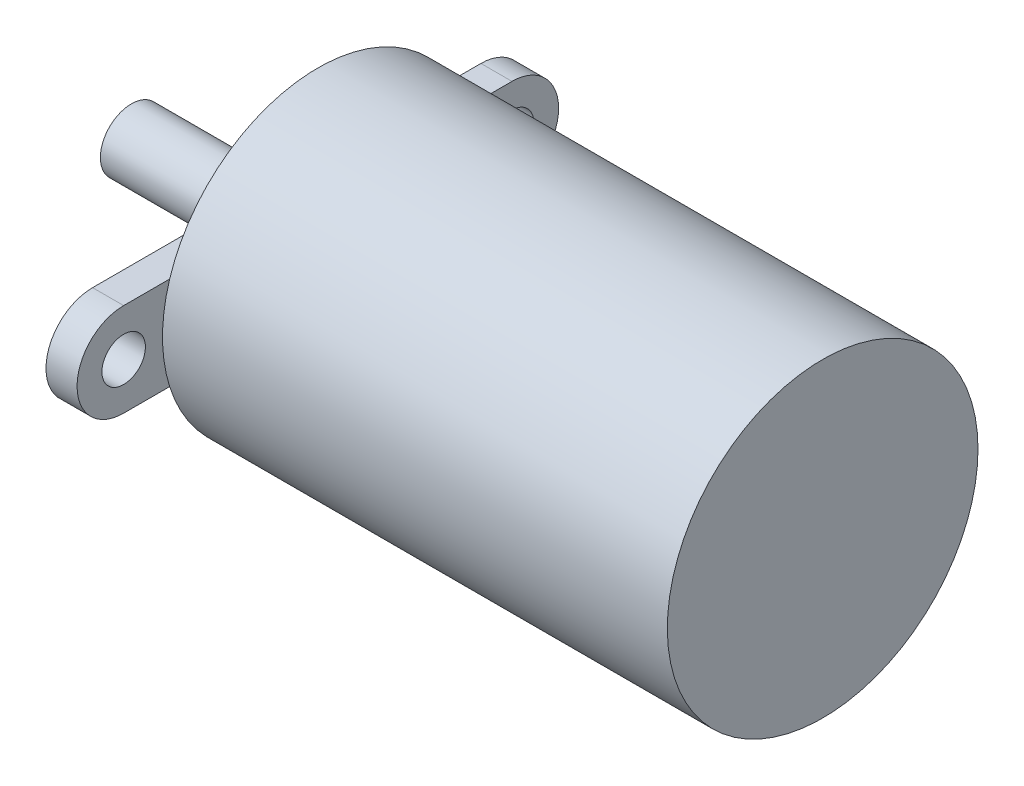
SolidWorks part; units mm, degrees
material "ABS"
ref_plane "Front" through (0, 0, 0) normal (0, 0, 1) x (1, 0, 0)
ref_plane "Top" through (0, 0, 0) normal (0, 1, 0) x (1, 0, 0)
ref_plane "Right" through (0, 0, 0) normal (1, 0, 0) x (0, 0, -1)
sketch "Sketch1" plane through (0, 0, 0) normal (1, 0, 0) x (0, 0, -1)
  circle A0 centre (0, 0) radius 10
  dimension "D1" = 20
extrude "Boss-Extrude1" add sketch "Sketch1" along normal blind 32.5
sketch "Sketch2" plane through (0, 0, 0) normal (-1, 0, 0) x (0, 0, 1)
  line L0 (-12.5, 0) -> (12.5, 0) construction
  line L1 (-12.5, 3) -> (12.5, 3)
  line L2 (-12.5, -3) -> (12.5, -3)
  arc A0 (-12.5, 3) -> (-12.5, -3) centre (-12.5, 0) ccw
  arc A1 (12.5, -3) -> (12.5, 3) centre (12.5, 0) ccw
  point P2 (0, 0)
  dimension "D1" = 3
  dimension "D2" = 25
extrude "Boss-Extrude2" add sketch "Sketch2" along normal blind 2
hole_wizard "Ø2.8 (2.8) Diameter Hole1" positions "Sketch4" profile "Sketch3" hole size "Ø2.8" standard "Ansi Metric"
sketch "Sketch4" plane through (-2, 0, 0) normal (-1, 0, 0) x (0, 0, 1)
  arc A0 (-12.5, 3) -> (-12.5, -3) centre (-12.5, 0) ccw construction
  arc A1 (12.5, -3) -> (12.5, 3) centre (12.5, 0) ccw construction
  point P0 (-12.5, 0)
  point P1 (12.5, 0)
  dimension "D1" = 0
  dimension "D2" = 0
sketch "Sketch3" plane through (-2, 0, -12.5) normal (0, 1, 0) x (0, 0, 1)
  line L0 (0, 0) -> (0, 70.8412)
  line L1 (0, 70.8412) -> (1.4, 70)
  line L2 (1.4, 70) -> (1.4, 0)
  line L5 (1.4, 0) -> (0, 0)
  line L10 (0, 70.8412) -> (-1.4, 70) construction
  line L11 (0, -6.35) -> (0, 107.95) construction
  dimension "Hole Dia." = 2.8
  dimension "Hole Depth" = 70
  dimension "Drill Angle" = 118
sketch "Sketch5" plane through (-2, 0, 0) normal (-1, 0, 0) x (0, 0, 1)
  circle A0 centre (0, 0) radius 4
  dimension "D1" = 8
extrude "Boss-Extrude3" add sketch "Sketch5" along normal blind 2
sketch "Sketch6" plane through (-4, 0, 0) normal (-1, 0, 0) x (0, 0, 1)
  circle A0 centre (0, 0) radius 2
  dimension "D1" = 4
extrude "Boss-Extrude4" add sketch "Sketch6" along normal blind 8
